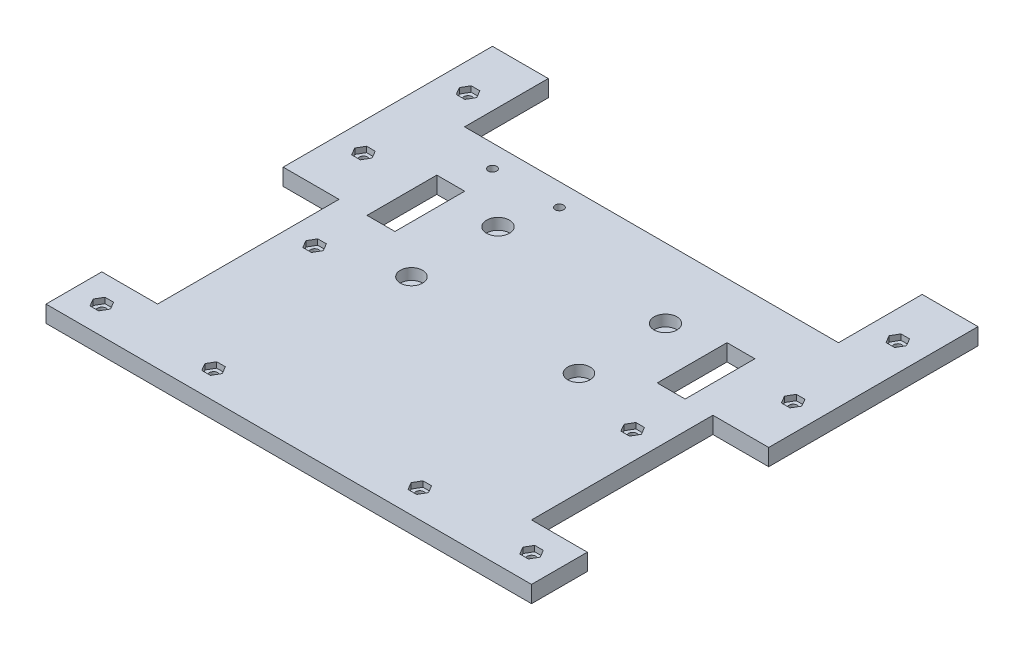
SolidWorks part; units mm, degrees
ref_plane "Alzado" through (0, 0, 0) normal (0, 0, 1) x (1, 0, 0)
ref_plane "Planta" through (0, 0, 0) normal (0, 1, 0) x (1, 0, 0)
ref_plane "Vista lateral" through (0, 0, 0) normal (1, 0, 0) x (0, 0, -1)
sketch "Croquis1" plane through (0, 0, 0) normal (0, 1, 0) x (1, 0, 0)
  line L0 (0, 0) -> (174, 0)
  line L1 (174, 0) -> (174, 20)
  line L2 (0, 0) -> (0, 20)
  line L3 (0, 20) -> (20, 20)
  line L4 (174, 20) -> (154, 20)
  line L5 (20, 20) -> (20, 85)
  line L6 (154, 20) -> (154, 85)
  line L7 (20, 85) -> (0, 85)
  line L8 (154, 85) -> (174, 85)
  line L9 (0, 85) -> (0, 160)
  line L10 (174, 85) -> (174, 160)
  line L11 (0, 160) -> (20, 160)
  line L12 (174, 160) -> (154, 160)
  line L13 (20, 160) -> (20, 130)
  line L14 (20, 130) -> (154, 130)
  line L15 (154, 130) -> (154, 160)
  dimension "D1" = 174
  dimension "D2" = 20
  dimension "D3" = 20
  dimension "D4" = 20
  dimension "D5" = 20
  dimension "D6" = 65
  dimension "D7" = 65
  dimension "D8" = 75
  dimension "D9" = 30
extrude "Saliente-Extruir1" add sketch "Croquis1" along normal blind 6
sketch "Croquis3" plane through (0, 6, 0) normal (0, 1, 0) x (1, 0, 0)
  line L0 (10, 160) -> (10, 85) construction
  line L1 (20, 160) -> (0, 160) construction
  line L2 (0, 85) -> (20, 85) construction
  line L3 (10, 85) -> (10, 122.5) construction
  line L4 (10, 122.5) -> (10, 141.25) construction
  line L5 (10, 141.25) -> (10, 103.75) construction
  line L6 (0, 20) -> (20, 20) construction
  line L7 (13.1, 141.25) -> (11.55, 143.9347)
  line L8 (11.55, 143.9347) -> (8.45, 143.9347)
  line L9 (8.45, 143.9347) -> (6.9, 141.25)
  line L10 (6.9, 141.25) -> (8.45, 138.5653)
  line L11 (8.45, 138.5653) -> (11.55, 138.5653)
  line L12 (11.55, 138.5653) -> (13.1, 141.25)
  line L13 (13.1, 103.75) -> (11.55, 106.4347)
  line L14 (11.55, 106.4347) -> (8.45, 106.4347)
  line L15 (8.45, 106.4347) -> (6.9, 103.75)
  line L16 (6.9, 103.75) -> (8.45, 101.0653)
  line L17 (8.45, 101.0653) -> (11.55, 101.0653)
  line L18 (11.55, 101.0653) -> (13.1, 103.75)
  line L19 (20, 20) -> (10, 20) construction
  line L20 (10, 20) -> (10, 0) construction
  line L21 (0, 0) -> (174, 0) construction
  line L22 (10, 20) -> (10, 10) construction
  line L23 (87, 0) -> (87, 20) construction
  line L24 (13.1, 10) -> (11.55, 12.6847)
  line L25 (11.55, 12.6847) -> (8.45, 12.6847)
  line L26 (8.45, 12.6847) -> (6.9, 10)
  line L27 (6.9, 10) -> (8.45, 7.3153)
  line L28 (8.45, 7.3153) -> (11.55, 7.3153)
  line L29 (11.55, 7.3153) -> (13.1, 10)
  line L30 (162.45, 101.0653) -> (160.9, 103.75)
  line L31 (165.55, 101.0653) -> (162.45, 101.0653)
  line L32 (167.1, 103.75) -> (165.55, 101.0653)
  line L33 (165.55, 106.4347) -> (167.1, 103.75)
  line L34 (162.45, 106.4347) -> (165.55, 106.4347)
  line L35 (160.9, 103.75) -> (162.45, 106.4347)
  line L36 (162.45, 138.5653) -> (160.9, 141.25)
  line L37 (165.55, 138.5653) -> (162.45, 138.5653)
  line L38 (167.1, 141.25) -> (165.55, 138.5653)
  line L39 (165.55, 143.9347) -> (167.1, 141.25)
  line L40 (162.45, 143.9347) -> (165.55, 143.9347)
  line L41 (160.9, 141.25) -> (162.45, 143.9347)
  line L42 (162.45, 7.3153) -> (160.9, 10)
  line L43 (165.55, 7.3153) -> (162.45, 7.3153)
  line L44 (167.1, 10) -> (165.55, 7.3153)
  line L45 (165.55, 12.6847) -> (167.1, 10)
  line L46 (162.45, 12.6847) -> (165.55, 12.6847)
  line L47 (160.9, 10) -> (162.45, 12.6847)
  circle A0 centre (10, 141.25) radius 3.1 construction
  circle A1 centre (10, 103.75) radius 3.1 construction
  circle A2 centre (10, 10) radius 3.1 construction
extrude "Cortar-Extruir1" cut sketch "Croquis3" against normal blind 2
sketch "Croquis4" plane through (0, 6, 0) normal (0, 1, 0) x (1, 0, 0)
  line L0 (162.45, 7.3153) -> (165.55, 7.3153) construction
  line L1 (165.55, 7.3153) -> (167.1, 10) construction
  line L2 (167.1, 10) -> (165.55, 12.6847) construction
  line L3 (165.55, 12.6847) -> (162.45, 12.6847) construction
  line L4 (162.45, 12.6847) -> (160.9, 10) construction
  line L5 (160.9, 10) -> (162.45, 7.3153) construction
  line L6 (162.45, 101.0653) -> (165.55, 101.0653) construction
  line L7 (165.55, 101.0653) -> (167.1, 103.75) construction
  line L8 (167.1, 103.75) -> (165.55, 106.4347) construction
  line L9 (165.55, 106.4347) -> (162.45, 106.4347) construction
  line L10 (162.45, 106.4347) -> (160.9, 103.75) construction
  line L11 (160.9, 103.75) -> (162.45, 101.0653) construction
  line L12 (162.45, 138.5653) -> (165.55, 138.5653) construction
  line L13 (165.55, 138.5653) -> (167.1, 141.25) construction
  line L14 (167.1, 141.25) -> (165.55, 143.9347) construction
  line L15 (165.55, 143.9347) -> (162.45, 143.9347) construction
  line L16 (0, 20) -> (0, 0)
  line L17 (0, 0) -> (174, 0)
  line L18 (174, 0) -> (174, 20)
  line L19 (174, 20) -> (154, 20)
  line L20 (154, 20) -> (154, 85)
  line L21 (154, 85) -> (174, 85)
  line L22 (174, 85) -> (174, 160)
  line L23 (174, 160) -> (154, 160)
  line L24 (154, 160) -> (154, 130)
  line L25 (154, 130) -> (20, 130)
  line L26 (20, 130) -> (20, 160)
  line L27 (20, 160) -> (0, 160)
  line L28 (0, 160) -> (0, 85)
  line L29 (0, 85) -> (20, 85)
  line L30 (20, 85) -> (20, 20)
  line L31 (20, 20) -> (0, 20)
  line L32 (0, 20) -> (0, 0)
  line L33 (0, 0) -> (174, 0)
  line L34 (174, 0) -> (174, 20)
  line L35 (174, 20) -> (154, 20)
  line L36 (154, 20) -> (154, 85)
  line L37 (154, 85) -> (174, 85)
  line L38 (174, 85) -> (174, 160)
  line L39 (174, 160) -> (154, 160)
  line L40 (154, 160) -> (154, 130)
  line L41 (154, 130) -> (20, 130)
  line L42 (20, 130) -> (20, 160)
  line L43 (20, 160) -> (0, 160)
  line L44 (0, 160) -> (0, 85)
  line L45 (0, 85) -> (20, 85)
  line L46 (20, 85) -> (20, 20)
  line L47 (20, 20) -> (0, 20)
  line L48 (162.45, 143.9347) -> (160.9, 141.25) construction
  line L49 (160.9, 141.25) -> (162.45, 138.5653) construction
  line L50 (11.55, 138.5653) -> (13.1, 141.25) construction
  line L51 (13.1, 141.25) -> (11.55, 143.9347) construction
  line L52 (11.55, 143.9347) -> (8.45, 143.9347) construction
  line L53 (8.45, 143.9347) -> (6.9, 141.25) construction
  line L54 (6.9, 141.25) -> (8.45, 138.5653) construction
  line L55 (8.45, 138.5653) -> (11.55, 138.5653) construction
  line L56 (11.55, 101.0653) -> (13.1, 103.75) construction
  line L57 (13.1, 103.75) -> (11.55, 106.4347) construction
  line L58 (11.55, 106.4347) -> (8.45, 106.4347) construction
  line L59 (8.45, 106.4347) -> (6.9, 103.75) construction
  line L60 (6.9, 103.75) -> (8.45, 101.0653) construction
  line L61 (8.45, 101.0653) -> (11.55, 101.0653) construction
  line L62 (11.55, 7.3153) -> (13.1, 10) construction
  line L63 (13.1, 10) -> (11.55, 12.6847) construction
  line L64 (11.55, 12.6847) -> (8.45, 12.6847) construction
  line L65 (8.45, 12.6847) -> (6.9, 10) construction
  line L66 (6.9, 10) -> (8.45, 7.3153) construction
  line L67 (8.45, 7.3153) -> (11.55, 7.3153) construction
  line L68 (162.45, 7.3153) -> (165.55, 7.3153)
  line L69 (165.55, 7.3153) -> (167.1, 10)
  line L70 (167.1, 10) -> (165.55, 12.6847)
  line L71 (165.55, 12.6847) -> (162.45, 12.6847)
  line L72 (162.45, 12.6847) -> (160.9, 10)
  line L73 (160.9, 10) -> (162.45, 7.3153)
  line L74 (162.45, 101.0653) -> (165.55, 101.0653)
  line L75 (165.55, 101.0653) -> (167.1, 103.75)
  line L76 (167.1, 103.75) -> (165.55, 106.4347)
  line L77 (165.55, 106.4347) -> (162.45, 106.4347)
  line L78 (162.45, 106.4347) -> (160.9, 103.75)
  line L79 (160.9, 103.75) -> (162.45, 101.0653)
  line L80 (162.45, 138.5653) -> (165.55, 138.5653)
  line L81 (165.55, 138.5653) -> (167.1, 141.25)
  line L82 (167.1, 141.25) -> (165.55, 143.9347)
  line L83 (165.55, 143.9347) -> (162.45, 143.9347)
  line L84 (162.45, 143.9347) -> (160.9, 141.25)
  line L85 (160.9, 141.25) -> (162.45, 138.5653)
  line L86 (11.55, 138.5653) -> (13.1, 141.25)
  line L87 (13.1, 141.25) -> (11.55, 143.9347)
  line L88 (11.55, 143.9347) -> (8.45, 143.9347)
  line L89 (8.45, 143.9347) -> (6.9, 141.25)
  line L90 (6.9, 141.25) -> (8.45, 138.5653)
  line L91 (8.45, 138.5653) -> (11.55, 138.5653)
  line L92 (11.55, 101.0653) -> (13.1, 103.75)
  line L93 (13.1, 103.75) -> (11.55, 106.4347)
  line L94 (11.55, 106.4347) -> (8.45, 106.4347)
  line L95 (8.45, 106.4347) -> (6.9, 103.75)
  line L96 (6.9, 103.75) -> (8.45, 101.0653)
  line L97 (8.45, 101.0653) -> (11.55, 101.0653)
  line L98 (11.55, 7.3153) -> (13.1, 10)
  line L99 (13.1, 10) -> (11.55, 12.6847)
  line L100 (11.55, 12.6847) -> (8.45, 12.6847)
  line L101 (8.45, 12.6847) -> (6.9, 10)
  line L102 (6.9, 10) -> (8.45, 7.3153)
  line L103 (8.45, 7.3153) -> (11.55, 7.3153)
  dimension "D1" = 0
extrude "Cortar-Extruir3" cut sketch "Croquis4" along normal blind 2 from offset 6 contours L102 L103 L98 L99 L100 L101 | L96 L97 L92 L93 L94 L95 | L90 L91 L86 L87 L88 L89 | L84 L85 L80 L81 L82 L83 | L78 L79 L74 L75 L76 L77 | L72 L73 L68 L69 L70 L71 offset against normal yes
sketch "Croquis5" plane through (0, 6, 0) normal (0, 1, 0) x (1, 0, 0)
  circle A0 centre (10, 141.25) radius 1.5
  circle A1 centre (10, 103.75) radius 1.5
  circle A2 centre (10, 10) radius 1.5
  circle A3 centre (164, 103.75) radius 1.5
  circle A4 centre (164, 141.25) radius 1.5
  circle A5 centre (164, 10) radius 1.5
extrude "Cortar-Extruir4" cut sketch "Croquis5" against normal blind 32
sketch "Croquis6" plane through (0, 6, 0) normal (0, 1, 0) x (1, 0, 0)
  line L0 (13.1, 10) -> (160.9, 10) construction
  line L1 (160.9, 10) -> (87, 10) construction
  line L2 (87, 10) -> (13.1, 10) construction
  line L3 (13.1, 10) -> (50.05, 10) construction
  line L4 (50.05, 10) -> (123.95, 10) construction
  line L6 (53.15, 10) -> (51.6, 12.6847)
  line L7 (51.6, 12.6847) -> (48.5, 12.6847)
  line L8 (48.5, 12.6847) -> (46.95, 10)
  line L9 (46.95, 10) -> (48.5, 7.3153)
  line L10 (48.5, 7.3153) -> (51.6, 7.3153)
  line L11 (51.6, 7.3153) -> (53.15, 10)
  line L12 (127.05, 10) -> (125.5, 12.6847)
  line L13 (125.5, 12.6847) -> (122.4, 12.6847)
  line L14 (122.4, 12.6847) -> (120.85, 10)
  line L15 (120.85, 10) -> (122.4, 7.3153)
  line L16 (122.4, 7.3153) -> (125.5, 7.3153)
  line L17 (125.5, 7.3153) -> (127.05, 10)
  circle A0 centre (50.05, 10) radius 3.1 construction
  circle A1 centre (123.95, 10) radius 3.1 construction
extrude "Cortar-Extruir5" cut sketch "Croquis6" against normal blind 2
sketch "Croquis7" plane through (0, 0, 0) normal (0, -1, 0) x (1, 0, 0)
  line L0 (13.1, -10) -> (160.9, -10) construction
  line L1 (160.9, -10) -> (87, -10) construction
  line L2 (87, -10) -> (123.95, -10) construction
  line L3 (87, -10) -> (13.1, -10) construction
  line L4 (13.1, -10) -> (50.05, -10) construction
  line L6 (53.15, -10) -> (51.6, -7.3153)
  line L7 (51.6, -7.3153) -> (48.5, -7.3153)
  line L8 (48.5, -7.3153) -> (46.95, -10)
  line L9 (46.95, -10) -> (48.5, -12.6847)
  line L10 (48.5, -12.6847) -> (51.6, -12.6847)
  line L11 (51.6, -12.6847) -> (53.15, -10)
  line L12 (127.05, -10) -> (125.5, -7.3153)
  line L13 (125.5, -7.3153) -> (122.4, -7.3153)
  line L14 (122.4, -7.3153) -> (120.85, -10)
  line L15 (120.85, -10) -> (122.4, -12.6847)
  line L16 (122.4, -12.6847) -> (125.5, -12.6847)
  line L17 (125.5, -12.6847) -> (127.05, -10)
  circle A0 centre (50.05, -10) radius 3.1 construction
  circle A1 centre (123.95, -10) radius 3.1 construction
extrude "Cortar-Extruir7" cut sketch "Croquis7" against normal blind 2
sketch "Croquis9" plane through (0, 2, 0) normal (0, -1, 0) x (1, 0, 0)
  line L0 (53.15, -10) -> (46.95, -10) construction
  line L1 (127.05, -10) -> (120.85, -10) construction
  circle A0 centre (123.95, -10) radius 1.5
  circle A1 centre (50.05, -10) radius 1.5
  dimension "D1" = 3
  dimension "D2" = 3
extrude "Cortar-Extruir8" cut sketch "Croquis9" against normal blind 2
sketch "Croquis10" plane through (0, 6, 0) normal (0, 1, 0) x (1, 0, 0)
  line L0 (10, 141.25) -> (10, 103.75) construction
  line L1 (10, 103.75) -> (10, 66.25) construction
  line L2 (10, 141.25) -> (0, 141.25) construction
  line L3 (0, 160) -> (0, 85) construction
  line L4 (10, 66.25) -> (30, 66.25) construction
  line L5 (154, 66.25) -> (144, 66.25) construction
  line L6 (33.1, 66.25) -> (31.55, 68.9347)
  line L7 (31.55, 68.9347) -> (28.45, 68.9347)
  line L8 (28.45, 68.9347) -> (26.9, 66.25)
  line L9 (26.9, 66.25) -> (28.45, 63.5653)
  line L10 (28.45, 63.5653) -> (31.55, 63.5653)
  line L11 (31.55, 63.5653) -> (33.1, 66.25)
  line L12 (154, 20) -> (154, 85) construction
  line L14 (147.1, 66.25) -> (145.55, 68.9347)
  line L15 (145.55, 68.9347) -> (142.45, 68.9347)
  line L16 (142.45, 68.9347) -> (140.9, 66.25)
  line L17 (140.9, 66.25) -> (142.45, 63.5653)
  line L18 (142.45, 63.5653) -> (145.55, 63.5653)
  line L19 (145.55, 63.5653) -> (147.1, 66.25)
  circle A0 centre (30, 66.25) radius 3.1 construction
  circle A1 centre (144, 66.25) radius 3.1 construction
  dimension "D1" = 37.5
  dimension "D2" = 20
  dimension "D3" = 10
extrude "Cortar-Extruir9" cut sketch "Croquis10" against normal blind 2
sketch "Croquis11" plane through (0, 0, 0) normal (0, -1, 0) x (1, 0, 0)
  line L0 (145.55, -63.5653) -> (147.1, -66.25) construction
  line L1 (147.1, -66.25) -> (145.55, -68.9347) construction
  line L2 (145.55, -68.9347) -> (142.45, -68.9347) construction
  line L3 (142.45, -68.9347) -> (140.9, -66.25) construction
  line L4 (140.9, -66.25) -> (142.45, -63.5653) construction
  line L5 (142.45, -63.5653) -> (145.55, -63.5653) construction
  line L6 (31.55, -63.5653) -> (33.1, -66.25) construction
  line L7 (33.1, -66.25) -> (31.55, -68.9347) construction
  line L8 (31.55, -68.9347) -> (28.45, -68.9347) construction
  line L9 (28.45, -68.9347) -> (26.9, -66.25) construction
  line L10 (26.9, -66.25) -> (28.45, -63.5653) construction
  line L11 (28.45, -63.5653) -> (31.55, -63.5653) construction
  line L12 (145.55, -63.5653) -> (147.1, -66.25)
  line L13 (147.1, -66.25) -> (145.55, -68.9347)
  line L14 (145.55, -68.9347) -> (142.45, -68.9347)
  line L15 (142.45, -68.9347) -> (140.9, -66.25)
  line L16 (140.9, -66.25) -> (142.45, -63.5653)
  line L17 (142.45, -63.5653) -> (145.55, -63.5653)
  line L18 (31.55, -63.5653) -> (33.1, -66.25)
  line L19 (33.1, -66.25) -> (31.55, -68.9347)
  line L20 (31.55, -68.9347) -> (28.45, -68.9347)
  line L21 (28.45, -68.9347) -> (26.9, -66.25)
  line L22 (26.9, -66.25) -> (28.45, -63.5653)
  line L23 (28.45, -63.5653) -> (31.55, -63.5653)
extrude "Cortar-Extruir10" cut sketch "Croquis11" against normal blind 2
sketch "Croquis12" plane through (0, 2, 0) normal (0, -1, 0) x (1, 0, 0)
  line L0 (26.9, -66.25) -> (33.1, -66.25) construction
  line L1 (33.1, -66.25) -> (140.9, -66.25) construction
  line L2 (140.9, -66.25) -> (147.1, -66.25) construction
  circle A0 centre (144, -66.25) radius 1.5
  circle A1 centre (30, -66.25) radius 1.5
  dimension "D1" = 3
  dimension "D2" = 3
extrude "Cortar-Extruir11" cut sketch "Croquis12" against normal blind 2
sketch "Croquis13" plane through (0, 6, 0) normal (0, 1, 0) x (1, 0, 0)
  line L0 (20, 130) -> (154, 130) construction
  line L1 (20, 130) -> (20, 160) construction
  line L2 (154, 130) -> (87, 130) construction
  line L3 (87, 130) -> (87, 105) construction
  line L4 (87, 105) -> (117.01, 105) construction
  circle A0 centre (117.01, 105) radius 4.1
  circle A1 centre (56.99, 105) radius 4.1
  dimension "D3" = 8.2
  dimension "D1" = 25
  dimension "D2" = 30.01
extrude "Cortar-Extruir12" cut sketch "Croquis13" against normal blind 4
sketch "Croquis14" plane through (0, 2, 0) normal (0, 1, 0) x (1, 0, 0)
  circle A3 centre (117.01, 105) radius 1.5
  circle A4 centre (56.99, 105) radius 1.5
  dimension "D3" = 3
  dimension "D4" = 3
extrude "Cortar-Extruir13" cut sketch "Croquis14" against normal blind 4
sketch "Croquis15" plane through (0, 6, 0) normal (0, 1, 0) x (1, 0, 0)
  line L0 (56.99, 105) -> (56.99, 73.98) construction
  line L1 (56.99, 73.98) -> (117.01, 73.98) construction
  circle A0 centre (56.99, 105) radius 1.5 construction
  circle A1 centre (56.99, 105) radius 1.5
  circle A2 centre (56.99, 73.98) radius 4
  circle A3 centre (117.01, 105) radius 1.5 construction
  circle A4 centre (117.01, 105) radius 1.5
  circle A5 centre (117.01, 73.98) radius 4
  dimension "D2" = 8
  dimension "D1" = 31.02
  dimension "D3" = 8
extrude "Cortar-Extruir14" cut sketch "Croquis15" against normal blind 4
sketch "Croquis16" plane through (0, 2, 0) normal (0, 1, 0) x (1, 0, 0)
  circle A0 centre (56.99, 73.98) radius 1.5
  circle A1 centre (117.01, 73.98) radius 1.5
  dimension "D1" = 3
  dimension "D2" = 3
extrude "Cortar-Extruir15" cut sketch "Croquis16" against normal blind 4
sketch "Croquis17" plane through (0, 6, 0) normal (0, 1, 0) x (1, 0, 0)
  line L0 (20, 130) -> (40, 130.0439) construction
  line L1 (154, 130) -> (20, 130) construction
  line L2 (20, 130) -> (20, 160) construction
  line L3 (40, 130.0439) -> (40, 110.0439) construction
  line L4 (87, 130) -> (87, 127.0426) construction
  line L5 (40, 110.0439) -> (30, 110.0439)
  line L6 (40, 110.0439) -> (40, 85.0439)
  line L7 (40, 85.0439) -> (30, 85.0439)
  line L8 (30, 110.0439) -> (30, 85.0439)
  line L9 (134, 85.0439) -> (144, 85.0439)
  line L10 (134, 110.0439) -> (144, 110.0439)
  line L11 (144, 110.0439) -> (144, 85.0439)
  line L12 (134, 110.0439) -> (134, 85.0439)
  dimension "D1" = 20
  dimension "D2" = 25
  dimension "D3" = 10
extrude "Cortar-Extruir16" cut sketch "Croquis17" against normal blind 11.3
sketch "Croquis18" plane through (0, 6, 0) normal (0, 1, 0) x (1, 0, 0)
  line L0 (20, 130) -> (50, 130) construction
  line L1 (154, 130) -> (20, 130) construction
  line L2 (50, 130) -> (50, 122) construction
  line L3 (38, 122) -> (62, 122)
  circle A0 centre (38, 122) radius 1.5
  circle A1 centre (62, 122) radius 1.5
  point P10 (50, 122)
  dimension "D4" = 3
  dimension "D5" = 3
  dimension "D1" = 30
  dimension "D2" = 8
  dimension "D3" = 24
extrude "Cortar-Extruir17" cut sketch "Croquis18" against normal blind 14
